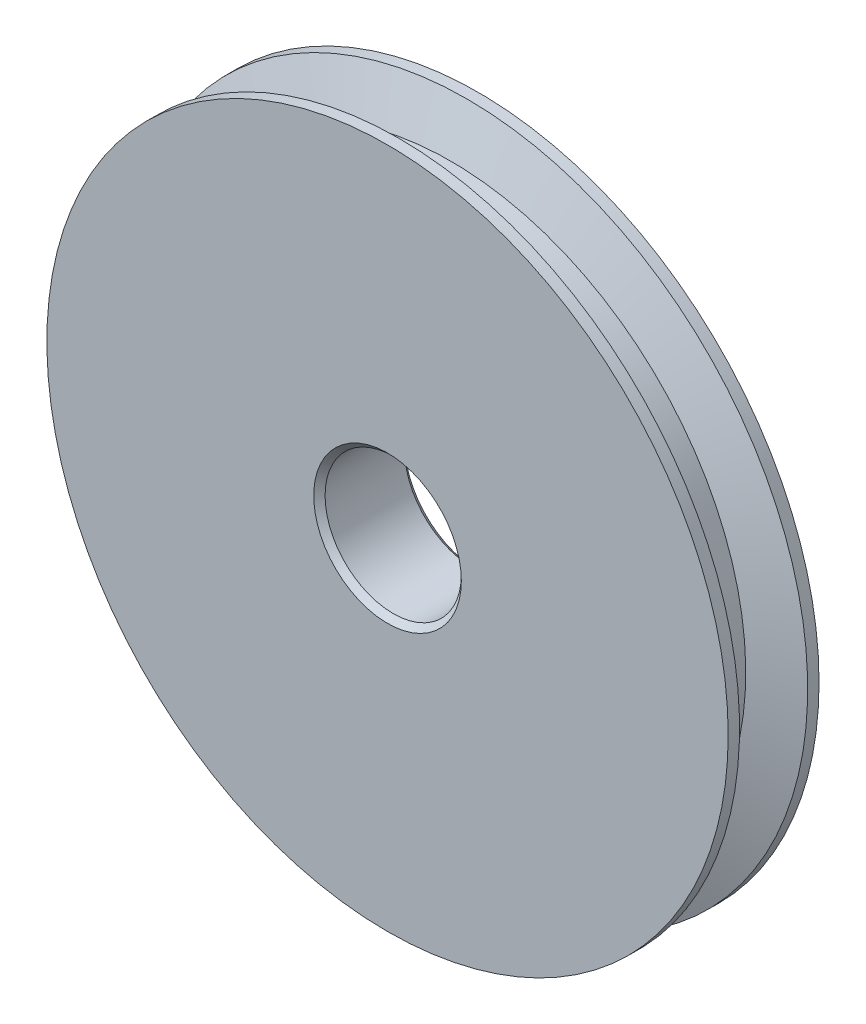
SolidWorks part; units mm, degrees
material "6061-T6 (SS)"
ref_plane "Front Plane" through (0, 0, 0) normal (0, 0, 1) x (1, 0, 0)
ref_plane "Top Plane" through (0, 0, 0) normal (0, 1, 0) x (1, 0, 0)
ref_plane "Right Plane" through (0, 0, 0) normal (1, 0, 0) x (0, 0, -1)
sketch "Sketch1" plane through (0, 0, 0) normal (0, 0, 1) x (1, 0, 0)
  circle A0 centre (0, 0) radius 47.625
  circle A1 centre (0, 0) radius 9.525
  dimension "D1" = 95.25
  dimension "D2" = 19.05
extrude "Extrude1" add sketch "Sketch1" along normal mid plane 12.7
sketch "Sketch2" plane through (0, 0, 0) normal (1, 0, 0) x (0, 0, -1)
  line L0 (-4.7625, 47.625) -> (4.7625, 47.625)
  line L2 (4.7625, 47.625) -> (2.4513, 41.275)
  line L3 (2.4513, 41.275) -> (-2.4513, 41.275)
  line L4 (-2.4513, 41.275) -> (-4.7625, 47.625)
  line L5 (-6.35, 0) -> (6.35, 0) construction
  line L6 (-6.35, 47.625) -> (-6.35, -47.625) construction
  line L7 (6.35, -47.625) -> (6.35, 47.625) construction
  point P2 (0, 47.625)
  point P5 (0, 41.275)
  dimension "D1" = 47.625
  dimension "D2" = 6.35
  dimension "D3" = 9.525
  dimension "D4" = 40
chamfer "Chamfer1" distance 0.7937 angle 45 2 edges at (9.525, 0, -6.35) (9.525, 0, 6.35)
revolve "Cut-Revolve1" cut sketch "Sketch2" angle 360 about L5
